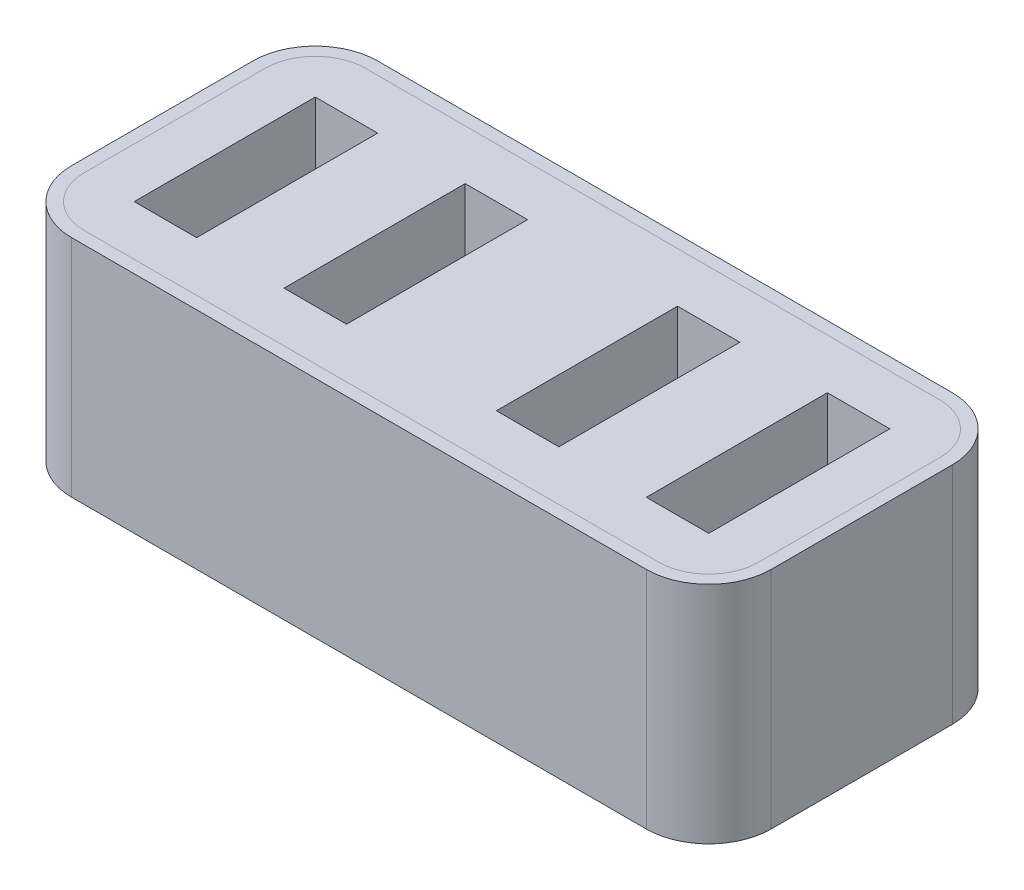
SolidWorks part; units mm, degrees
material "PE Low Density Film"
ref_plane "Front Plane" through (0, 0, 0) normal (0, 0, 1) x (1, 0, 0)
ref_plane "Top Plane" through (0, 0, 0) normal (0, 1, 0) x (1, 0, 0)
ref_plane "Right Plane" through (0, 0, 0) normal (1, 0, 0) x (0, 0, -1)
sketch "Sketch1" plane through (0, 0, 0) normal (0, 1, 0) x (1, 0, 0)
  line L0 (-27, 7.25) -> (-27, -7.25)
  line L1 (-23, 12.25) -> (23, 12.25)
  line L2 (-28, 7.25) -> (-28, -7.25)
  line L3 (-23, -12.25) -> (23, -12.25)
  line L4 (28, 7.25) -> (28, -7.25)
  line L5 (-28, 12.25) -> (28, -12.25) construction
  line L6 (-28, -12.25) -> (28, 12.25) construction
  line L7 (-23, -11.25) -> (23, -11.25)
  line L8 (27, 7.25) -> (27, -7.25)
  line L9 (-23, 11.25) -> (23, 11.25)
  arc A0 (-28, -7.25) -> (-23, -12.25) centre (-23, -7.25) ccw
  arc A1 (-23, 12.25) -> (-28, 7.25) centre (-23, 7.25) ccw
  arc A2 (23, -12.25) -> (28, -7.25) centre (23, -7.25) ccw
  arc A3 (23, 12.25) -> (28, 7.25) centre (23, 7.25) cw
  arc A4 (-23, 11.25) -> (-27, 7.25) centre (-23, 7.25) ccw
  arc A5 (-27, -7.25) -> (-23, -11.25) centre (-23, -7.25) ccw
  arc A6 (23, -11.25) -> (27, -7.25) centre (23, -7.25) ccw
  arc A7 (23, 11.25) -> (27, 7.25) centre (23, 7.25) cw
  point P0 (0, 0)
  dimension "D3" = 5
  dimension "D1" = 24.5
  dimension "D2" = 56
  dimension "D4" = 1
extrude "Boss-Extrude1" add sketch "Sketch1" along normal blind 18
sketch "Sketch4" plane through (0, 0, 0) normal (0, 1, 0) x (1, 0, 0)
  line L0 (27, -7.25) -> (27, 7.25) construction
  line L1 (-23, -11.25) -> (23, -11.25) construction
  line L2 (-27, 7.25) -> (-27, -7.25) construction
  line L3 (23, 11.25) -> (-23, 11.25) construction
  line L4 (27, -7.25) -> (27, 7.25)
  line L5 (-23, -11.25) -> (23, -11.25)
  line L6 (-27, 7.25) -> (-27, -7.25)
  line L7 (23, 11.25) -> (-23, 11.25)
  arc A0 (27, 7.25) -> (23, 11.25) centre (23, 7.25) ccw construction
  arc A1 (23, -11.25) -> (27, -7.25) centre (23, -7.25) ccw construction
  arc A2 (-27, -7.25) -> (-23, -11.25) centre (-23, -7.25) ccw construction
  arc A3 (-23, 11.25) -> (-27, 7.25) centre (-23, 7.25) ccw construction
  arc A4 (27, 7.25) -> (23, 11.25) centre (23, 7.25) ccw
  arc A5 (23, -11.25) -> (27, -7.25) centre (23, -7.25) ccw
  arc A6 (-27, -7.25) -> (-23, -11.25) centre (-23, -7.25) ccw
  arc A7 (-23, 11.25) -> (-27, 7.25) centre (-23, 7.25) ccw
extrude "Boss-Extrude3" add sketch "Sketch4" along normal blind 18 separate body
sketch "Sketch2" plane through (0, 0, 0) normal (0, 1, 0) x (1, 0, 0)
  line L9 (-23, 7.25) -> (-18, 7.25)
  line L10 (-23, 7.25) -> (-23, -7.25)
  line L11 (-23, -7.25) -> (-18, -7.25)
  line L12 (-18, 7.25) -> (-18, -7.25)
  line L13 (-11, 7.25) -> (-6, 7.25)
  line L14 (-11, 7.25) -> (-11, -7.25)
  line L15 (-11, -7.25) -> (-6, -7.25)
  line L16 (-6, 7.25) -> (-6, -7.25)
  line L17 (23, 7.25) -> (18, 7.25)
  line L18 (23, 7.25) -> (23, -7.25)
  line L19 (23, -7.25) -> (18, -7.25)
  line L20 (18, 7.25) -> (18, -7.25)
  line L21 (11, 7.25) -> (6, 7.25)
  line L22 (11, 7.25) -> (11, -7.25)
  line L23 (11, -7.25) -> (6, -7.25)
  line L24 (6, 7.25) -> (6, -7.25)
  dimension "D1" = 5
  dimension "D2" = 7
  dimension "D3" = 12
  dimension "D4" = 7
  dimension "D5" = 14.5
  dimension "D6" = 6
  dimension "D7" = 7.25
extrude "Cut-Extrude1" cut sketch "Sketch2" against normal blind 10 from surface at 18 starting at face at (0, 18, 0)
